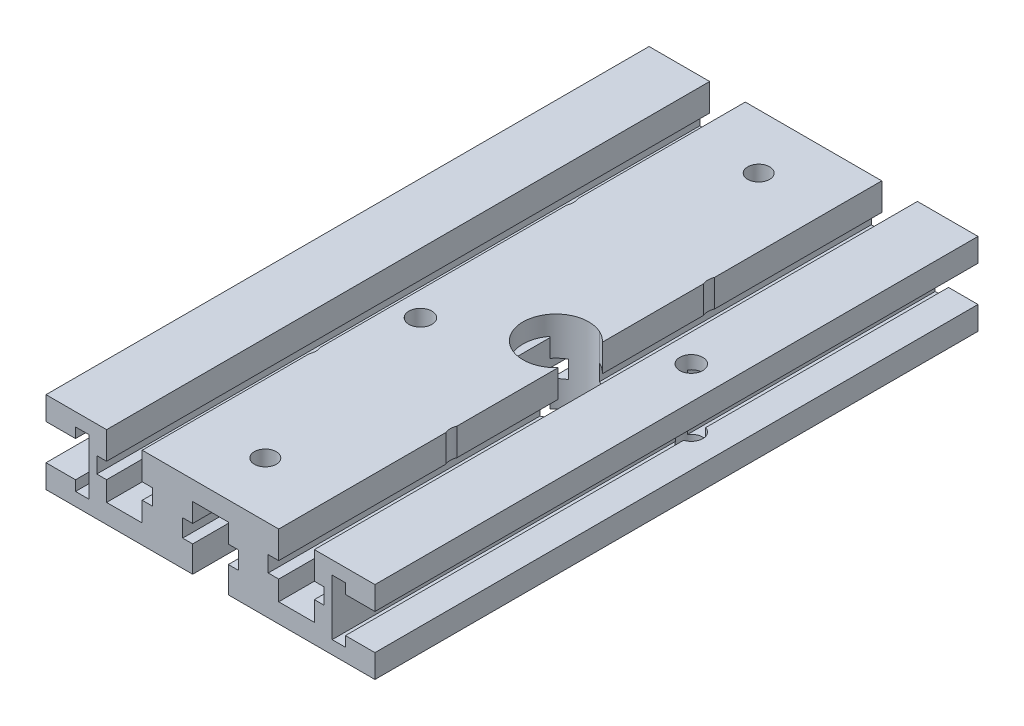
SolidWorks part; units mm, degrees
ref_plane "前视" through (0, 0, 0) normal (0, 0, 1) x (1, 0, 0)
ref_plane "上视" through (0, 0, 0) normal (0, 1, 0) x (1, 0, 0)
ref_plane "右视" through (0, 0, 0) normal (1, 0, 0) x (0, 0, -1)
sketch "草图1" plane through (0, 0, 0) normal (0, 0, 1) x (1, 0, 0)
  line L0 (0, 0) -> (26.75, 0)
  line L1 (0, 0) -> (0, 4.25)
  line L2 (0, 4.25) -> (5.3867, 4.25)
  line L3 (5.3867, 4.25) -> (5.3867, 2.4)
  line L4 (5.3867, 2.4) -> (7.8, 2.4)
  line L5 (7.8, 2.4) -> (7.8, 12.6)
  line L6 (7.8, 12.6) -> (5.3867, 12.6)
  line L7 (5.3867, 12.6) -> (5.3867, 10.75)
  line L8 (5.3867, 10.75) -> (0, 10.75)
  line L9 (0, 10.75) -> (0, 15)
  line L10 (0, 15) -> (11.0524, 15)
  line L11 (11.0524, 15) -> (11.0524, 10.0038)
  line L12 (11.0524, 10.0038) -> (9.2662, 10.0038)
  line L13 (9.2662, 10.0038) -> (9.2662, 7.0947)
  line L14 (9.2662, 7.0947) -> (11.0524, 7.0947)
  line L15 (11.0524, 7.0947) -> (11.0524, 3.5)
  line L16 (11.0524, 3.5) -> (17.5524, 3.5)
  line L17 (17.5524, 3.5) -> (17.5524, 7.0947)
  line L18 (17.5524, 7.0947) -> (19.4662, 7.0947)
  line L19 (19.4662, 7.0947) -> (19.4662, 10.0038)
  line L20 (19.4662, 10.0038) -> (17.5524, 10.0038)
  line L21 (17.5524, 10.0038) -> (17.5524, 15)
  line L22 (17.5524, 15) -> (30, 15)
  line L23 (26.75, 0) -> (26.75, 4.7964)
  line L24 (26.75, 4.7964) -> (24.9265, 4.7964)
  line L25 (24.9265, 4.7964) -> (24.9265, 8.0234)
  line L26 (24.9265, 8.0234) -> (26.75, 8.0234)
  line L27 (26.75, 8.0234) -> (26.75, 11.5)
  line L28 (26.75, 11.5) -> (30, 11.5)
  line L29 (30, 15) -> (42.4476, 15)
  line L30 (30, 11.5) -> (33.25, 11.5)
  line L32 (33.25, 8.0234) -> (33.25, 11.5)
  line L33 (35.0735, 8.0234) -> (33.25, 8.0234)
  line L34 (35.0735, 4.7964) -> (35.0735, 8.0234)
  line L35 (33.25, 4.7964) -> (35.0735, 4.7964)
  line L36 (33.25, 0) -> (33.25, 4.7964)
  line L37 (42.4476, 10.0038) -> (42.4476, 15)
  line L38 (40.5338, 10.0038) -> (42.4476, 10.0038)
  line L39 (40.5338, 7.0947) -> (40.5338, 10.0038)
  line L40 (42.4476, 7.0947) -> (40.5338, 7.0947)
  line L41 (42.4476, 3.5) -> (42.4476, 7.0947)
  line L42 (48.9476, 3.5) -> (42.4476, 3.5)
  line L43 (48.9476, 7.0947) -> (48.9476, 3.5)
  line L44 (50.7338, 7.0947) -> (48.9476, 7.0947)
  line L45 (50.7338, 10.0038) -> (50.7338, 7.0947)
  line L46 (48.9476, 10.0038) -> (50.7338, 10.0038)
  line L47 (48.9476, 15) -> (48.9476, 10.0038)
  line L48 (60, 15) -> (48.9476, 15)
  line L49 (60, 10.75) -> (60, 15)
  line L50 (54.6133, 10.75) -> (60, 10.75)
  line L51 (54.6133, 12.6) -> (54.6133, 10.75)
  line L52 (52.2, 12.6) -> (54.6133, 12.6)
  line L53 (52.2, 2.4) -> (52.2, 12.6)
  line L54 (54.6133, 2.4) -> (52.2, 2.4)
  line L55 (54.6133, 4.25) -> (54.6133, 2.4)
  line L56 (60, 4.25) -> (54.6133, 4.25)
  line L57 (60, 0) -> (60, 4.25)
  line L58 (60, 0) -> (33.25, 0)
  dimension "D1" = 6.5
  dimension "D2" = 7.8
  dimension "D3" = 15
  dimension "D4" = 6.5
  dimension "D5" = 11.5
  dimension "D6" = 2.4
  dimension "D7" = 10.2
  dimension "D8" = 15
  dimension "D9" = 2.4
  dimension "D10" = 4.25
  dimension "D11" = 11.5
  dimension "D12" = 60
  dimension "D13" = 3.25
extrude "凸台-拉伸1" add sketch "草图1" along normal blind 110
hole_wizard "Ø5.5 (5.5) 直径孔1" positions "草图3" profile "草图2" hole size "Ø5.5" standard "Gb" end condition through all
sketch "草图3" plane through (0, 0, 0) normal (0, -1, 0) x (-1, 0, 0)
  line L0 (-33.25, -110) -> (-60, -110) construction
  line L1 (-60, -110) -> (-60, 0) construction
  line L2 (0, -110) -> (0, 0) construction
  point P0 (-45, -78.5)
  point P2 (-45, -31.5)
  point P4 (-15, -31.5)
  point P6 (-15, -78.5)
  dimension "D1" = 31.5
  dimension "D2" = 78.5
  dimension "D3" = 15
  dimension "D4" = 15
sketch "草图2" plane through (45, 0, 78.5) normal (1, 0, 0) x (0, 0, -1)
  line L0 (0, 0) -> (0, 15)
  line L1 (0, 15) -> (2.75, 15)
  line L2 (2.75, 15) -> (2.75, 0)
  line L5 (2.75, 0) -> (0, 0)
  line L11 (0, -6.35) -> (0, 107.95) construction
  dimension "通孔孔直径" = 5.5
  dimension "通孔孔深度" = 15
hole_wizard "Ø4.0 (4) 直径孔1" positions "草图5" profile "草图4" hole size "Ø4.0" standard "Gb" end condition through all
sketch "草图5" plane through (0, 11.5, 0) normal (0, -1, 0) x (-1, 0, 0)
  line L0 (0, -110) -> (0, 0) construction
  line L2 (-26.75, -110) -> (-33.25, -110) construction
  line L3 (-26.75, 0) -> (-33.25, 0) construction
  point P0 (-30, -100)
  point P2 (-30, -10)
  dimension "D1" = 30
  dimension "D2" = 10
  dimension "D3" = 10
sketch "草图4" plane through (30, 11.5, 100) normal (1, 0, 0) x (0, 0, -1)
  line L0 (0, 0) -> (0, 3.5)
  line L1 (0, 3.5) -> (2, 3.5)
  line L2 (2, 3.5) -> (2, 0)
  line L5 (2, 0) -> (0, 0)
  line L11 (0, -6.35) -> (0, 107.95) construction
  dimension "通孔孔直径" = 4
  dimension "通孔孔深度" = 3.5
hole_wizard "Ø12.0 (12) 直径孔1" positions "草图7" profile "草图6" hole size "Ø12.0" standard "Gb" end condition through all
sketch "草图7" plane through (0, 0, 0) normal (0, -1, 0) x (-1, 0, 0)
  line L3 (-33.25, -110) -> (-60, -110) construction
  line L6 (-60, -110) -> (-60, 0) construction
  point P0 (-38, -55)
  dimension "D1" = 55
  dimension "D2" = 22
sketch "草图6" plane through (38, 0, 55) normal (1, 0, 0) x (0, 0, -1)
  line L0 (0, 0) -> (0, 15)
  line L1 (0, 15) -> (6, 15)
  line L2 (6, 15) -> (6, 0)
  line L5 (6, 0) -> (0, 0)
  line L11 (0, -6.35) -> (0, 107.95) construction
  dimension "通孔孔直径" = 12
  dimension "通孔孔深度" = 15
hole_wizard "M5 螺纹孔1" positions "草图9" profile "草图8" tap size "M5" standard "Gb" end condition through all
sketch "草图9" plane through (0, 0, 0) normal (0, -1, 0) x (-1, 0, 0)
  line L0 (-33.25, -110) -> (-60, -110) construction
  line L1 (-60, -110) -> (-60, 0) construction
  line L2 (0, -110) -> (-26.75, -110) construction
  line L3 (0, -110) -> (0, 0) construction
  point P0 (-54, -46.3)
  point P2 (-22, -63.7)
  dimension "D1" = 63.7
  dimension "D2" = 6
  dimension "D3" = 46.3
  dimension "D4" = 22
sketch "草图8" plane through (54, 0, 46.3) normal (1, 0, 0) x (0, 0, -1)
  line L0 (0, 0) -> (0, 15)
  line L1 (0, 15) -> (2.1, 15)
  line L2 (2.1, 15) -> (2.1, 0)
  line L5 (2.1, 0) -> (0, 0)
  line L11 (0, -6.35) -> (0, 107.95) construction
  dimension "通孔螺纹孔钻头直径" = 4.2
  dimension "通孔螺纹孔钻头深度" = 15
cosmetic thread "孔螺蚊线1" parameters "D2"=5
cosmetic thread "孔螺蚊线2" parameters "D2"=5
